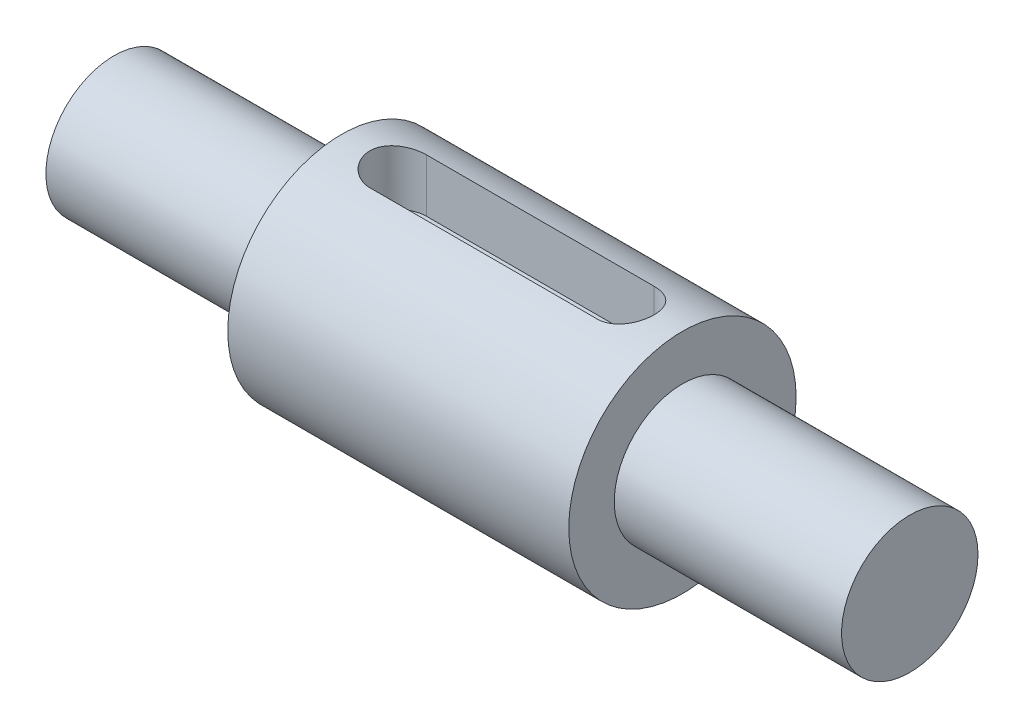
SolidWorks part; units mm, degrees
ref_plane "Ön Düzlem" through (0, 0, 0) normal (0, 0, 1) x (1, 0, 0)
ref_plane "Üst Düzlem" through (0, 0, 0) normal (0, 1, 0) x (1, 0, 0)
ref_plane "Sağ Düzlem" through (0, 0, 0) normal (1, 0, 0) x (0, 0, -1)
sketch "Çizim1" plane through (0, 0, 0) normal (1, 0, 0) x (0, 0, -1)
  circle A0 centre (0, 0) radius 60
  dimension "D1" = 120
extrude "Yükseklik-Ekstrüzyon1" add sketch "Çizim1" along normal blind 200
sketch "Çizim2" plane through (200, 0, 0) normal (1, 0, 0) x (0, 0, -1)
  circle A0 centre (0, 0) radius 100
  dimension "D1" = 200
extrude "Yükseklik-Ekstrüzyon2" add sketch "Çizim2" along normal blind 300
sketch "Çizim3" plane through (500, 0, 0) normal (1, 0, 0) x (0, 0, -1)
  circle A0 centre (0, 0) radius 60
  dimension "D1" = 120
extrude "Yükseklik-Ekstrüzyon3" add sketch "Çizim3" along normal blind 200
ref_plane "Düzlem1" through (0, 50, 0) normal (0, 1, 0) x (1, 0, 0)
sketch "Çizim4" plane through (0, 50, 0) normal (0, 1, 0) x (1, 0, 0)
  line L0 (350, 100) -> (350, -100) construction
  line L1 (500, 100) -> (200, 100) construction
  line L2 (200, -100) -> (500, -100) construction
  line L3 (250, 0) -> (450, 0) construction
  line L4 (250, 25) -> (450, 25)
  line L5 (250, -25) -> (450, -25)
  arc A0 (250, 25) -> (250, -25) centre (250, 0) ccw
  arc A1 (450, -25) -> (450, 25) centre (450, 0) ccw
  point P9 (350, 0)
  dimension "D2" = 25
  dimension "D1" = 200
extrude "Kes-Ekstrüzyon1" cut sketch "Çizim4" along normal blind 200
